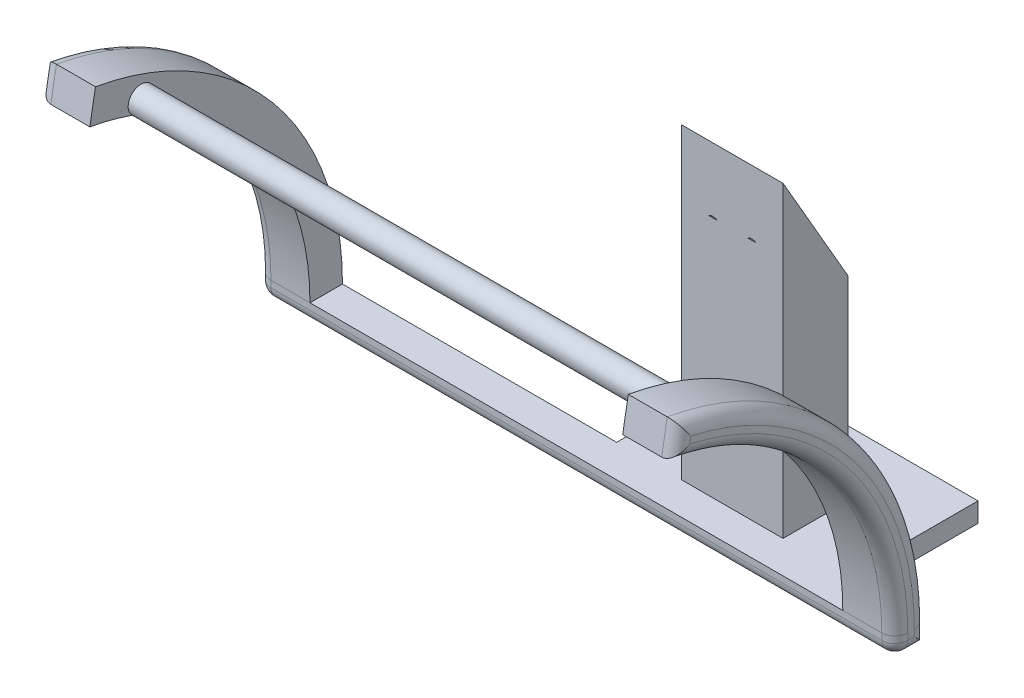
SolidWorks part; units mm, degrees
ref_plane "Front Plane" through (0, 0, 0) normal (0, 0, 1) x (1, 0, 0)
ref_plane "Top Plane" through (0, 0, 0) normal (0, 1, 0) x (1, 0, 0)
ref_plane "Right Plane" through (0, 0, 0) normal (1, 0, 0) x (0, 0, -1)
sketch "Sketch1" plane through (0, 0, 0) normal (0, 1, 0) x (1, 0, 0)
  line L0 (-8.4368, 20.25) -> (-8.4368, 0.25) construction
  line L1 (-26.2418, 20.25) -> (9.3682, 20.25)
  line L2 (-26.2418, 20.25) -> (-26.2418, 0.25)
  line L3 (-26.2418, 0.25) -> (9.3682, 0.25)
  line L4 (9.3682, 20.25) -> (9.3682, 0.25)
  line L5 (-38.4368, 0.25) -> (21.5632, 0.25)
  line L6 (-38.4368, 0.25) -> (-38.4368, -4.75)
  line L7 (-38.4368, -4.75) -> (21.5632, -4.75)
  line L8 (21.5632, 0.25) -> (21.5632, -4.75)
  line L9 (-23.1318, 20.25) -> (6.2583, 20.25) construction
  line L11 (-38.4368, -4.75) -> (-76.4368, -4.75)
  line L12 (-38.4368, -4.75) -> (-38.4368, 0.25)
  line L13 (-38.4368, 0.25) -> (-76.4368, 0.25)
  line L14 (-76.4368, -4.75) -> (-76.4368, 0.25)
  point P10 (-8.4368, 0.25)
  dimension "D1" = 20
  dimension "D2" = 35.61
  dimension "D3" = 60
  dimension "D4" = 5
  dimension "D5" = 38
extrude "Boss-Extrude1" add sketch "Sketch1" along normal blind 3 contours L8 L5 L3 L6 L7 | L1 L0 L5 L4 | L0 L1 L2 L3 | L12 L11 L14 L13
ref_plane "Plane1" through (21.5632, 0, 0) normal (1, 0, 0) x (0, 0, -1)
sketch "Sketch2" plane through (21.5632, 0, 0) normal (1, 0, 0) x (0, 0, -1)
  line L0 (-4.75, 3) -> (-30.75, 3) construction
  line L1 (-30.75, 3) -> (-45.75, 3) construction
  line L2 (-37.7622, 48.3012) -> (-38.6304, 43.3771)
  line L3 (-4.75, 3) -> (0.25, 3)
  circle A0 centre (-45.75, 3) radius 22.5 construction
  arc A1 (-4.75, 3) -> (-38.6304, 43.3771) centre (-45.75, 3) ccw
  arc A2 (0.25, 3) -> (-37.7622, 48.3012) centre (-45.75, 3) ccw
  dimension "D3" = 45
  dimension "D1" = 26
  dimension "D2" = 15
ref_plane "Plane2" through (-8.4368, 0, 0) normal (1, 0, 0) x (0, 0, -1)
sketch "Sketch3" plane through (0, 0, 0) normal (0, -1, 0) x (1, 0, 0)
  circle A0 centre (-20.4847, -8.75) radius 1.5
  circle A1 centre (-8.4349, -16.25) radius 1.5
  circle A2 centre (3.6149, -8.75) radius 1.5
  dimension "D1" = 3
extrude "Cut-Extrude1" cut sketch "Sketch3" against normal blind 5
sketch "Sketch7" plane through (0, 3, 0) normal (0, 1, 0) x (1, 0, 0)
  line L0 (-26.2418, 20.25) -> (-26.2418, 0.25) construction
  line L1 (-16.2418, 10.25) -> (-0.6318, 10.25)
  line L2 (-16.2418, 10.25) -> (-16.2418, 0.25)
  line L3 (-16.2418, 0.25) -> (-0.6318, 0.25)
  line L4 (-0.6318, 10.25) -> (-0.6318, 0.25)
  line L5 (9.3682, 20.25) -> (9.3682, 0.25) construction
  line L6 (-38.4368, -4.75) -> (21.5632, -4.75) construction
  dimension "D1" = 10
  dimension "D2" = 10
  dimension "D3" = 5
  dimension "D4" = 10
extrude "Boss-Extrude4" add sketch "Sketch7" along normal blind 30
sketch "Sketch8" plane through (-16.2418, 0, 0) normal (-1, 0, 0) x (0, 0, 1)
  line L0 (-10.25, 33) -> (-0.25, 50.3205)
  line L1 (-0.25, 33) -> (-0.25, 50.3205)
  line L2 (-10.25, 33) -> (-0.25, 33) construction
  line L3 (-10.25, 33) -> (-0.25, 33)
  dimension "D1" = 60
extrude "Boss-Extrude5" add sketch "Sketch8" against normal up to surface (15.61 mm away) up to face at (-0.6318, 18, -5.25)
sketch "Sketch9" plane through (0, 12.6884, -21.9769) normal (0, 0.5, -0.866) x (1, 0, 0)
  line L0 (-16.2418, -33.4538) -> (-0.6318, -33.4538) construction
  line L1 (-16.2418, -43.4538) -> (-16.2418, -23.4538) construction
  line L2 (-0.6318, -23.4538) -> (-0.6318, -43.4538) construction
  line L3 (-8.4368, -23.4538) -> (-8.4368, -43.4538) construction
  line L4 (-0.6318, -23.4538) -> (-16.2418, -23.4538) construction
  line L5 (-0.6318, -43.4538) -> (-16.2418, -43.4538) construction
  circle A0 centre (-11.4368, -33.4538) radius 1.5
  circle A1 centre (-5.4368, -33.4538) radius 1.5
  dimension "D1" = 3
  dimension "D2" = 3
  dimension "D3" = 6
  dimension "D4" = 3
extrude "Cut-Extrude2" cut sketch "Sketch9" against normal blind 5
extrude "Boss-Extrude6" add sketch "Sketch2" against normal blind 8
ref_plane "Plane3" through (-27.4368, 0, 0) normal (-1, 0, 0) x (0, 0, 1)
mirror "Mirror1" about plane through (-27.4368, 0, 0) normal (-1, 0, 0) of "Boss-Extrude6"
fillet "Fillet4" radius 2 13 edges at (-76.4368, 1.5, -0.25) (-76.4368, 32.5682, 10.512) (-76.4368, 45.8391, 38.1963) (-76.4368, 29.3543, 14.3422) (-76.4368, 1.5, 4.75) (-76.4368, 0, 2.25) (21.5632, 1.5, 4.75) (21.5632, 29.3543, 14.3422) (21.5632, 45.8391, 38.1963) (21.5632, 32.5682, 10.512) (21.5632, 1.5, -0.25) (21.5632, 0, 2.25) (-27.4368, 0, 4.75)
sketch "Sketch10" plane through (-68.4368, 0, 0) normal (1, 0, 0) x (0, 0, -1)
  line L0 (-22.8312, 42.884) -> (-23.762, 37.6053)
  line L1 (-38.6304, 43.3771) -> (-22.8312, 42.884) construction
  line L2 (-4.75, 3) -> (0.25, 3)
  line L3 (-37.7622, 48.3012) -> (-38.6304, 43.3771)
  line L4 (-4.75, 3) -> (0.25, 3)
  line L5 (-37.7622, 48.3012) -> (-38.6304, 43.3771)
  line L6 (-23.762, 37.6053) -> (-37.7622, 48.3012) construction
  circle A0 centre (-30.7308, 43.1305) radius 2
  arc A2 (-4.75, 3) -> (-38.6304, 43.3771) centre (-45.75, 3) ccw
  arc A3 (0.25, 3) -> (-37.7622, 48.3012) centre (-45.75, 3) ccw
  arc A4 (-4.75, 3) -> (-38.6304, 43.3771) centre (-45.75, 3) ccw
  arc A5 (0.25, 3) -> (-37.7622, 48.3012) centre (-45.75, 3) ccw
  dimension "D2" = 4
  dimension "D1" = 0
extrude "Boss-Extrude7" add sketch "Sketch10" along normal up to surface (82 mm away) contours A0
